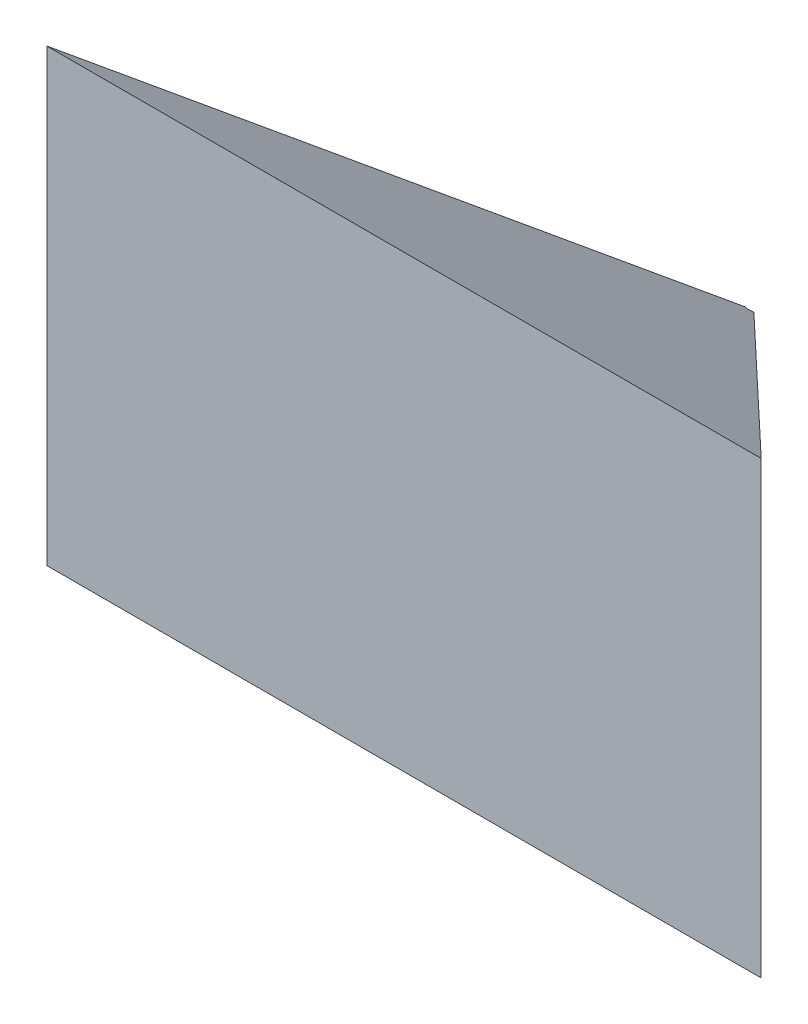
SolidWorks part; units mm, degrees
ref_plane "Front Plane" through (0, 0, 0) normal (0, 0, 1) x (1, 0, 0)
ref_plane "Top Plane" through (0, 0, 0) normal (0, 1, 0) x (1, 0, 0)
ref_plane "Right Plane" through (0, 0, 0) normal (1, 0, 0) x (0, 0, -1)
ref_axis "Axis1" through (0, 3540.0082, 0) along (0, -1, 0)
sketch "Sketch1" plane through (0, 0, -0.1) normal (0, 0, 1) x (1, 0, 0)
  line L5 (-17.9, 3.6) -> (-5.1, 3.6)
  line L6 (-17.9, 3.6) -> (-17.9, -3.6)
  line L7 (-17.9, -3.6) -> (-5.1, -3.6)
  line L8 (-5.1, 3.6) -> (-5.1, -3.6)
  line L9 (-17.9, 3.6) -> (-5.1, -3.6) construction
  line L10 (-17.9, -3.6) -> (-5.1, 3.6) construction
  line L11 (-11.5, 6.455) -> (-11.5, -6.455) construction
  line L13 (-21.0384, 0) -> (-2.0444, 0) construction
  line L14 (-14.5834, 6.455) -> (-8.4166, 6.455) construction
  line L15 (-8.4166, -6.455) -> (-14.5834, -6.455) construction
  arc A2 (-14.5834, 6.455) -> (-14.5834, -6.455) centre (-14.5834, 0) ccw construction
  point P0 (-11.5, 0)
  point P2 (-11.5, 6.455)
  point P10 (-2.0444, 0)
  point P11 (-11.5, -6.455)
  point P16 (-21.0384, 0)
  point P20 (-11.5, 0)
  point P21 (0, 0)
  point P22 (0, 0)
  point P23 (0, 0)
  point P24 (0, 0)
  point P25 (0, 0)
  dimension "D1" = 7.2
  dimension "D2" = 12.8
extrude "Boss-Extrude1" add sketch "Sketch1" along normal blind 10000 draft 45.6
sketch "Sketch2" plane through (0, 0, 0) normal (1, 0, 0) x (0, -1, 0)
  line L0 (-12631.7809, -19632.6062) -> (-3.6, 0.1)
  line L1 (-3.6, 0.1) -> (3.6, 0.1)
  line L2 (3.6, 0.1) -> (12631.7809, -19632.6062)
  line L3 (0, 0.1) -> (0, -20.4111) construction
  line L4 (-12631.7809, -19632.6062) -> (-20603.4318, 5804.7104)
  line L6 (-20603.4318, 5804.7104) -> (22327.5027, 5804.7104)
  line L9 (22327.5027, 5804.7104) -> (12631.7809, -19632.6062)
  line L11 (10215.2638, -9999.9) -> (3.6, 0.1) construction
  dimension "D1" = 65.5
  dimension "D4" = 32.75
extrude "Cut-Extrude1" cut sketch "Sketch2" against normal through all both and the other way through all
sketch "Sketch4" plane through (0, 0, 0) normal (1, 0, 0) x (0, 0, -1)
  line L0 (0, -200) -> (0, 200)
  arc A0 (0, 200) -> (0, -200) centre (0, 0) ccw
  point P6 (0, 0)
  dimension "D1" = 200
revolve "Cut-Revolve3" cut sketch "Sketch4" angle 360 about axis through (0, 3540.0082, 0) along (0, -1, 0)
equation "\"D4@Sketch2\"=\"D1@Sketch2\"/2"
